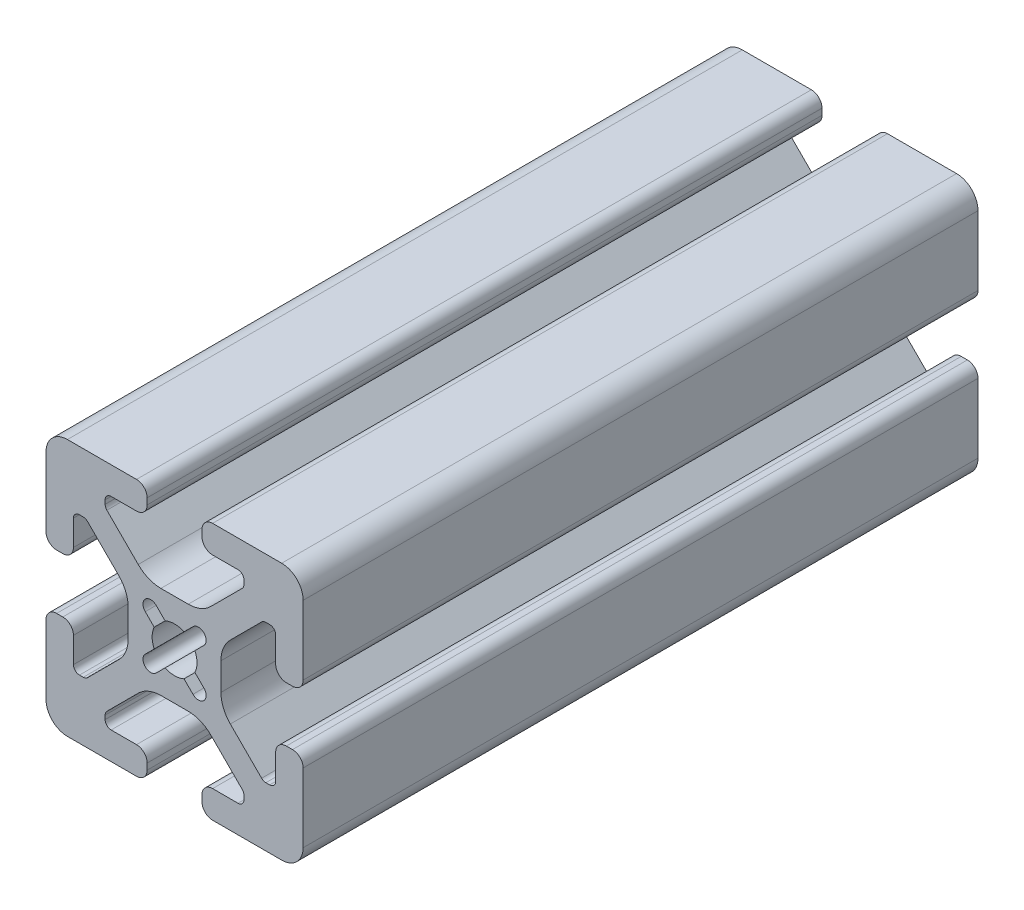
SolidWorks part; units mm, degrees
material "6061-T6 (SS)"
ref_plane "Front Plane" through (0, 0, 0) normal (0, 0, 1) x (1, 0, 0)
ref_plane "Top Plane" through (0, 0, 0) normal (0, 1, 0) x (1, 0, 0)
ref_plane "Right Plane" through (0, 0, 0) normal (1, 0, 0) x (0, 0, -1)
sketch "Sketch1" plane through (0, 0, 0) normal (0, 0, 1) x (1, 0, 0)
  line L0 (4.2456, 2.6398) -> (3.0178, 1.4017)
  line L1 (3.0179, -1.4014) -> (4.3433, -2.7269)
  line L2 (2.7269, -4.3433) -> (1.4014, -3.0179)
  line L3 (-1.4014, -3.0179) -> (-2.7269, -4.3433)
  line L4 (-4.3433, -2.7269) -> (-3.0179, -1.4014)
  line L5 (-3.0179, 1.4014) -> (-4.3433, 2.7269)
  line L6 (-2.7269, 4.3433) -> (-1.4014, 3.0179)
  line L7 (1.4017, 3.0178) -> (2.6398, 4.2456)
  line L8 (14.986, -5.6388) -> (14.986, -9.398)
  line L9 (14.097, -10.287) -> (13.5289, -10.287)
  line L10 (12.9003, -10.0266) -> (8.2608, -5.3872)
  line L11 (6.8697, -2.0285) -> (6.8697, 2.0285)
  line L12 (8.2608, 5.3872) -> (12.9003, 10.0266)
  line L13 (13.5289, 10.287) -> (14.097, 10.287)
  line L14 (14.986, 9.398) -> (14.986, 5.6388)
  line L15 (16.5608, 4.064) -> (17.4752, 4.064)
  line L16 (19.05, 5.6388) -> (19.05, 15.875)
  line L17 (15.875, 19.05) -> (5.6388, 19.05)
  line L18 (4.064, 17.4752) -> (4.064, 16.5608)
  line L19 (5.6388, 14.986) -> (9.398, 14.986)
  line L20 (10.287, 14.097) -> (10.287, 13.5289)
  line L21 (10.0266, 12.9003) -> (5.3872, 8.2608)
  line L22 (2.0285, 6.8697) -> (-2.0285, 6.8697)
  line L23 (-5.3872, 8.2608) -> (-10.0266, 12.9003)
  line L24 (-10.287, 13.5289) -> (-10.287, 14.097)
  line L25 (-9.398, 14.986) -> (-5.6388, 14.986)
  line L26 (-4.064, 16.5608) -> (-4.064, 17.4752)
  line L27 (-5.6388, 19.05) -> (-15.875, 19.05)
  line L28 (-19.05, 15.875) -> (-19.05, 5.6388)
  line L29 (-17.4752, 4.064) -> (-16.5608, 4.064)
  line L30 (-14.986, 5.6388) -> (-14.986, 9.398)
  line L31 (-14.097, 10.287) -> (-13.5289, 10.287)
  line L32 (-12.9003, 10.0266) -> (-8.2608, 5.3872)
  line L33 (-6.8697, 2.0285) -> (-6.8697, -2.0285)
  line L34 (-8.2608, -5.3872) -> (-12.9003, -10.0266)
  line L35 (-13.5289, -10.287) -> (-14.097, -10.287)
  line L36 (-14.986, -9.398) -> (-14.986, -5.6388)
  line L37 (-16.5608, -4.064) -> (-17.4752, -4.064)
  line L38 (-19.05, -5.6388) -> (-19.05, -15.875)
  line L39 (-15.875, -19.05) -> (-5.6388, -19.05)
  line L40 (-4.064, -17.4752) -> (-4.064, -16.5608)
  line L41 (-5.6388, -14.986) -> (-9.398, -14.986)
  line L42 (-10.287, -14.097) -> (-10.287, -13.5289)
  line L43 (-10.0266, -12.9003) -> (-5.3872, -8.2608)
  line L44 (-2.0285, -6.8697) -> (2.0285, -6.8697)
  line L45 (5.3872, -8.2608) -> (10.0266, -12.9003)
  line L46 (10.287, -13.5289) -> (10.287, -14.097)
  line L47 (9.398, -14.986) -> (5.6388, -14.986)
  line L48 (4.064, -16.5608) -> (4.064, -17.4752)
  line L49 (5.6388, -19.05) -> (15.875, -19.05)
  line L50 (19.05, -15.875) -> (19.05, -5.6388)
  line L51 (17.4752, -4.064) -> (16.5608, -4.064)
  arc A0 (4.2456, 2.6398) -> (2.6398, 4.2456) centre (3.5351, 3.5351) ccw
  arc A1 (1.4017, 3.0178) -> (-1.4014, 3.0179) centre (0, 0) ccw
  arc A2 (2.7269, -4.3433) -> (4.3433, -2.7269) centre (3.5351, -3.5351) ccw
  arc A3 (-3.0179, 1.4014) -> (-3.0179, -1.4014) centre (0, 0) ccw
  arc A4 (-4.3433, -2.7269) -> (-2.7269, -4.3433) centre (-3.5351, -3.5351) ccw
  arc A5 (-1.4014, -3.0179) -> (1.4014, -3.0179) centre (0, 0) ccw
  arc A6 (-2.7269, 4.3433) -> (-4.3433, 2.7269) centre (-3.5351, 3.5351) ccw
  arc A8 (16.5608, -4.064) -> (14.986, -5.6388) centre (16.5608, -5.6388) ccw
  arc A9 (14.097, -10.287) -> (14.986, -9.398) centre (14.097, -9.398) ccw
  arc A10 (12.9003, -10.0266) -> (13.5289, -10.287) centre (13.5289, -9.398) ccw
  arc A11 (6.8697, -2.0285) -> (8.2608, -5.3872) centre (11.6195, -2.0285) ccw
  arc A12 (8.2608, 5.3872) -> (6.8697, 2.0285) centre (11.6195, 2.0285) ccw
  arc A13 (13.5289, 10.287) -> (12.9003, 10.0266) centre (13.5289, 9.398) ccw
  arc A14 (14.986, 9.398) -> (14.097, 10.287) centre (14.097, 9.398) ccw
  arc A15 (14.986, 5.6388) -> (16.5608, 4.064) centre (16.5608, 5.6388) ccw
  arc A16 (17.4752, 4.064) -> (19.05, 5.6388) centre (17.4752, 5.6388) ccw
  arc A17 (19.05, 15.875) -> (15.875, 19.05) centre (15.875, 15.875) ccw
  arc A18 (5.6388, 19.05) -> (4.064, 17.4752) centre (5.6388, 17.4752) ccw
  arc A19 (4.064, 16.5608) -> (5.6388, 14.986) centre (5.6388, 16.5608) ccw
  arc A20 (10.287, 14.097) -> (9.398, 14.986) centre (9.398, 14.097) ccw
  arc A21 (10.0266, 12.9003) -> (10.287, 13.5289) centre (9.398, 13.5289) ccw
  arc A22 (2.0285, 6.8697) -> (5.3872, 8.2608) centre (2.0285, 11.6195) ccw
  arc A23 (-5.3872, 8.2608) -> (-2.0285, 6.8697) centre (-2.0285, 11.6195) ccw
  arc A24 (-10.287, 13.5289) -> (-10.0266, 12.9003) centre (-9.398, 13.5289) ccw
  arc A25 (-9.398, 14.986) -> (-10.287, 14.097) centre (-9.398, 14.097) ccw
  arc A26 (-5.6388, 14.986) -> (-4.064, 16.5608) centre (-5.6388, 16.5608) ccw
  arc A27 (-4.064, 17.4752) -> (-5.6388, 19.05) centre (-5.6388, 17.4752) ccw
  arc A28 (-15.875, 19.05) -> (-19.05, 15.875) centre (-15.875, 15.875) ccw
  arc A29 (-19.05, 5.6388) -> (-17.4752, 4.064) centre (-17.4752, 5.6388) ccw
  arc A30 (-16.5608, 4.064) -> (-14.986, 5.6388) centre (-16.5608, 5.6388) ccw
  arc A31 (-14.097, 10.287) -> (-14.986, 9.398) centre (-14.097, 9.398) ccw
  arc A32 (-12.9003, 10.0266) -> (-13.5289, 10.287) centre (-13.5289, 9.398) ccw
  arc A33 (-6.8697, 2.0285) -> (-8.2608, 5.3872) centre (-11.6195, 2.0285) ccw
  arc A34 (-8.2608, -5.3872) -> (-6.8697, -2.0285) centre (-11.6195, -2.0285) ccw
  arc A35 (-13.5289, -10.287) -> (-12.9003, -10.0266) centre (-13.5289, -9.398) ccw
  arc A36 (-14.986, -9.398) -> (-14.097, -10.287) centre (-14.097, -9.398) ccw
  arc A37 (-14.986, -5.6388) -> (-16.5608, -4.064) centre (-16.5608, -5.6388) ccw
  arc A38 (-17.4752, -4.064) -> (-19.05, -5.6388) centre (-17.4752, -5.6388) ccw
  arc A39 (-19.05, -15.875) -> (-15.875, -19.05) centre (-15.875, -15.875) ccw
  arc A40 (-5.6388, -19.05) -> (-4.064, -17.4752) centre (-5.6388, -17.4752) ccw
  arc A41 (-4.064, -16.5608) -> (-5.6388, -14.986) centre (-5.6388, -16.5608) ccw
  arc A42 (-10.287, -14.097) -> (-9.398, -14.986) centre (-9.398, -14.097) ccw
  arc A43 (-10.0266, -12.9003) -> (-10.287, -13.5289) centre (-9.398, -13.5289) ccw
  arc A44 (-2.0285, -6.8697) -> (-5.3872, -8.2608) centre (-2.0285, -11.6195) ccw
  arc A45 (5.3872, -8.2608) -> (2.0285, -6.8697) centre (2.0285, -11.6195) ccw
  arc A46 (10.287, -13.5289) -> (10.0266, -12.9003) centre (9.398, -13.5289) ccw
  arc A47 (9.398, -14.986) -> (10.287, -14.097) centre (9.398, -14.097) ccw
  arc A48 (5.6388, -14.986) -> (4.064, -16.5608) centre (5.6388, -16.5608) ccw
  arc A49 (4.064, -17.4752) -> (5.6388, -19.05) centre (5.6388, -17.4752) ccw
  arc A50 (15.875, -19.05) -> (19.05, -15.875) centre (15.875, -15.875) ccw
  arc A51 (19.05, -5.6388) -> (17.4752, -4.064) centre (17.4752, -5.6388) ccw
  arc A52 (3.0179, -1.4014) -> (3.0178, 1.4017) centre (0, 0) ccw
  dimension "D1" = 6.6548
extrude "Extrude1" add sketch "Sketch1" against normal blind 100
